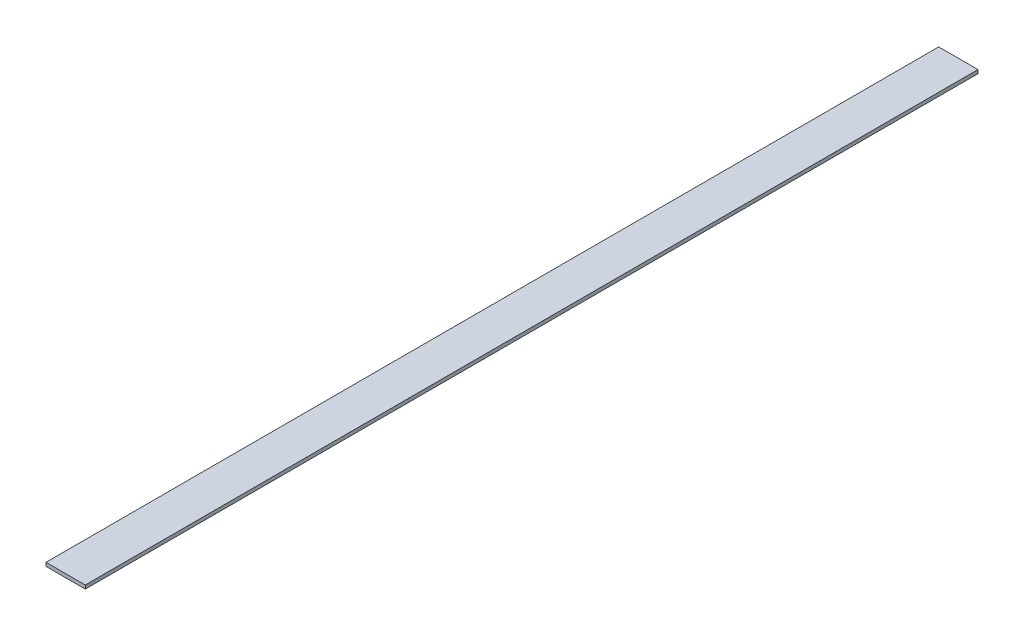
SolidWorks part; units mm, degrees
ref_plane "Front Plane" through (0, 0, 0) normal (0, 0, 1) x (1, 0, 0)
ref_plane "Top Plane" through (0, 0, 0) normal (0, 1, 0) x (1, 0, 0)
ref_plane "Right Plane" through (0, 0, 0) normal (1, 0, 0) x (0, 0, -1)
sketch "Sketch1" plane through (0, 0, 0) normal (0, 0, 1) x (1, 0, 0)
  line L1 (0, 0) -> (110, 0)
  line L2 (0, 0) -> (0, -10)
  line L3 (0, -10) -> (110, -10)
  line L4 (110, 0) -> (110, -10)
  dimension "D1" = 10
  dimension "D2" = 110
extrude "Boss-Extrude1" add sketch "Sketch1" along normal blind 2500
